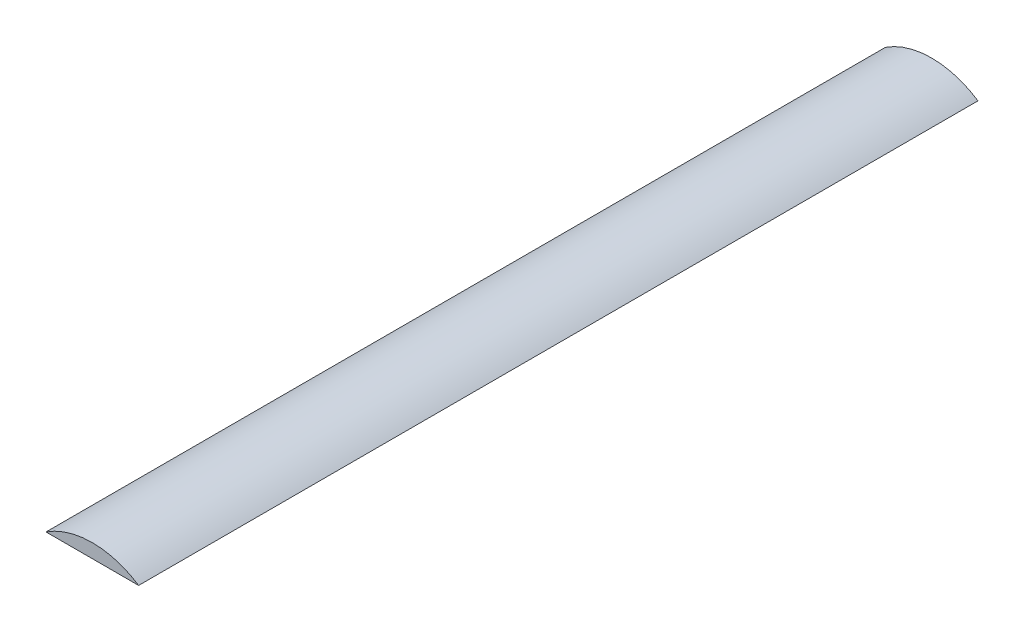
SolidWorks part; units mm, degrees
ref_plane "Front Plane" through (0, 0, 0) normal (0, 0, 1) x (1, 0, 0)
ref_plane "Top Plane" through (0, 0, 0) normal (0, 1, 0) x (1, 0, 0)
ref_plane "Right Plane" through (0, 0, 0) normal (1, 0, 0) x (0, 0, -1)
sketch "Sketch3" plane through (0, 0, 0) normal (0, 0, 1) x (1, 0, 0)
  circle A0 centre (0, 0) radius 1000
extrude "Boss-Extrude2" add sketch "Sketch3" along normal blind 10000
sketch "Sketch4" plane through (0, 0, 10000) normal (0, 0, 1) x (1, 0, 0)
  line L1 (-1291.02, 834) -> (1370.8769, 834)
  line L2 (-1291.02, 834) -> (-1291.02, -1052.7802)
  line L3 (-1291.02, -1052.7802) -> (1370.8769, -1052.7802)
  line L4 (1370.8769, 834) -> (1370.8769, -1052.7802)
  dimension "D1" = 834
extrude "Cut-Extrude1" cut sketch "Sketch4" against normal blind 11886 and the other way blind 1646
